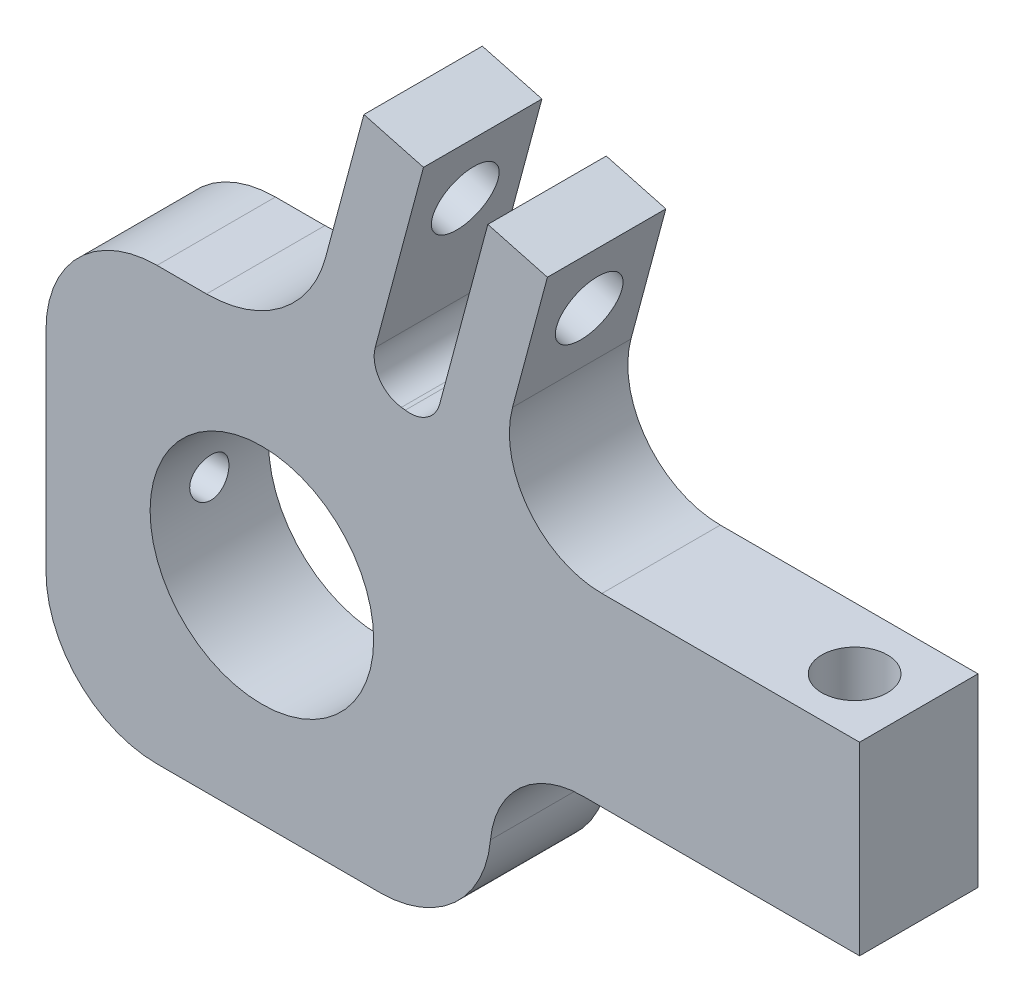
SolidWorks part; units mm, degrees
material "6061 Alloy"
ref_plane "Front Plane" through (0, 0, 0) normal (0, 0, 1) x (1, 0, 0)
ref_plane "Top Plane" through (0, 0, 0) normal (0, 1, 0) x (1, 0, 0)
ref_plane "Right Plane" through (0, 0, 0) normal (1, 0, 0) x (0, 0, -1)
sketch "Sketch1" plane through (0, 0, 0) normal (0, 0, 1) x (1, 0, 0)
  line L1 (0, 0) -> (96.52, 0)
  line L2 (0, 0) -> (0, -44.45)
  line L3 (0, -44.45) -> (96.52, -44.45)
  line L4 (96.52, 0) -> (96.52, -44.45)
  dimension "D1" = 44.45
  dimension "D2" = 96.52
extrude "Boss-Extrude1" add sketch "Sketch1" along normal mid plane 12.192
sketch "Sketch2" plane through (0, 0, 6.096) normal (0, 0, 1) x (1, 0, 0)
  circle A0 centre (22.225, -22.225) radius 11.5087
  dimension "D1" = 23.0175
  dimension "D2" = 22.225
  dimension "D3" = 22.225
extrude "Cut-Extrude1" cut sketch "Sketch2" against normal up to next
sketch "Sketch3" plane through (0, 0, 0) normal (0, 1, 0) x (1, 0, 0)
  line L1 (96.52, 6.096) -> (0, 6.096) construction
  line L2 (96.52, -6.096) -> (96.52, 6.096) construction
  circle A0 centre (77.4065, -0.254) radius 3.3782
  dimension "D1" = 6.7564
  dimension "D2" = 19.1135
  dimension "D3" = 6.35
extrude "Cut-Extrude2" cut sketch "Sketch3" against normal up to next
sketch "Sketch4" plane through (0, 0, 6.096) normal (0, 0, 1) x (1, 0, 0)
  line L0 (48.895, 0) -> (96.52, 0) construction
  line L1 (96.52, 0) -> (0, 0) construction
  line L2 (48.895, 6.35) -> (96.52, 6.35)
  line L3 (48.895, -6.35) -> (96.52, -6.35)
  line L4 (96.52, -34.925) -> (55.245, -34.925) construction
  line L5 (45.72, -34.925) -> (45.72, -44.45)
  line L8 (96.52, -44.45) -> (96.52, 0) construction
  line L9 (96.52, -44.45) -> (55.245, -44.45)
  line L10 (96.52, -25.4) -> (55.245, -25.4)
  line L11 (0, -44.45) -> (96.52, -44.45) construction
  line L12 (45.72, -44.45) -> (55.245, -44.45)
  arc A0 (48.895, 6.35) -> (48.895, -6.35) centre (48.895, 0) ccw
  arc A1 (96.52, -6.35) -> (96.52, 6.35) centre (96.52, 0) ccw
  arc A4 (96.52, -44.45) -> (96.52, -25.4) centre (96.52, -34.925) ccw
  arc A5 (55.245, -25.4) -> (45.72, -34.925) centre (55.245, -34.925) ccw
  point P5 (72.7075, 0)
  dimension "D1" = 6.35
  dimension "D3" = 9.525
  dimension "D2" = 47.625
  dimension "D4" = 41.275
extrude "Cut-Extrude3" cut sketch "Sketch4" against normal up to next
sketch "Sketch7" plane through (0, -6.35, 0) normal (0, 1, 0) x (1, 0, 0)
  line L0 (96.52, 6.096) -> (48.895, 6.096) construction
  line L1 (96.52, -6.096) -> (83.7565, -6.096)
  line L2 (96.52, -6.096) -> (96.52, 6.096)
  line L3 (96.52, 6.096) -> (83.7565, 6.096)
  line L4 (83.7565, -6.096) -> (83.7565, 6.096)
  dimension "D1" = 12.7635
extrude "Cut-Extrude5" cut sketch "Sketch7" against normal through all
fillet "Fillet1" radius 11.43 4 edges at (42.545, 0, 0) (45.72, -44.45, 0) (0, -44.45, 0) (0, 0, 0)
sketch "Sketch11" plane through (0, 0, 0) normal (-1, 0, 0) x (0, 0, 1)
  line L0 (6.096, -11.43) -> (6.096, -33.02) construction
  circle A0 centre (0, -22.225) radius 2.0193
  point P6 (6.096, -22.225)
  dimension "D1" = 4.0386
extrude "Cut-Extrude9" cut sketch "Sketch11" against normal up to next
sketch "Sketch14" plane through (0, 0, 0) normal (0, 0, 1) x (1, 0, 0)
  line L0 (45.0453, -5.4969) -> (51.6193, 19.0376)
  line L1 (26.2702, 0) -> (32.8442, 0)
  line L2 (35.2758, 0) -> (11.43, 0) construction
  line L3 (38.9116, -3.8534) -> (45.4856, 20.6811)
  line L4 (53.5567, 14.508) -> (48349.848, -12926.4443) construction
  line L6 (32.8442, 0) -> (38.8613, 22.4561)
  line L7 (38.8613, 22.4561) -> (32.7277, 24.0996)
  line L8 (32.7277, 24.0996) -> (26.2702, 0)
  line L10 (45.0453, -5.4969) -> (38.9116, -3.8534)
  line L11 (45.4856, 20.6811) -> (51.6193, 19.0376)
  arc A0 (44.031, -4.0821) -> (35.2758, 0) centre (35.2758, -11.43) ccw construction
  point P0 (44.483, 16.9393)
  point P2 (22.225, -22.225)
  dimension "D1" = 22.258
  dimension "D2" = 39.1643
  dimension "D3" = 75
  dimension "D4" = 25.4
  dimension "D5" = 6.35
  dimension "D6" = 6.858
  dimension "D7" = 6.35
extrude "Boss-Extrude2" add sketch "Sketch14" along normal mid plane 12.192
fillet "Fillet2" radius 3.175 2 edges at (32.8442, 0, 0) (39.7049, -0.893, 0)
fillet "Fillet3" radius 12.7 1 edges at (26.2702, 0, 0)
fillet "Fillet4" radius 9.525 1 edges at (45.1451, -5.1245, 0)
sketch "Sketch15" plane through (43.402, -11.6295, 0) normal (0.9659, -0.2588, 0) x (0, 0, -1)
  line L1 (-6.096, 31.749) -> (6.096, 31.749) construction
  circle A0 centre (0, 24.8097) radius 3.3782
  dimension "D1" = 6.7564
  dimension "D2" = 6.9393
extrude "Cut-Extrude10" cut sketch "Sketch15" against normal through all both and the other way through all
